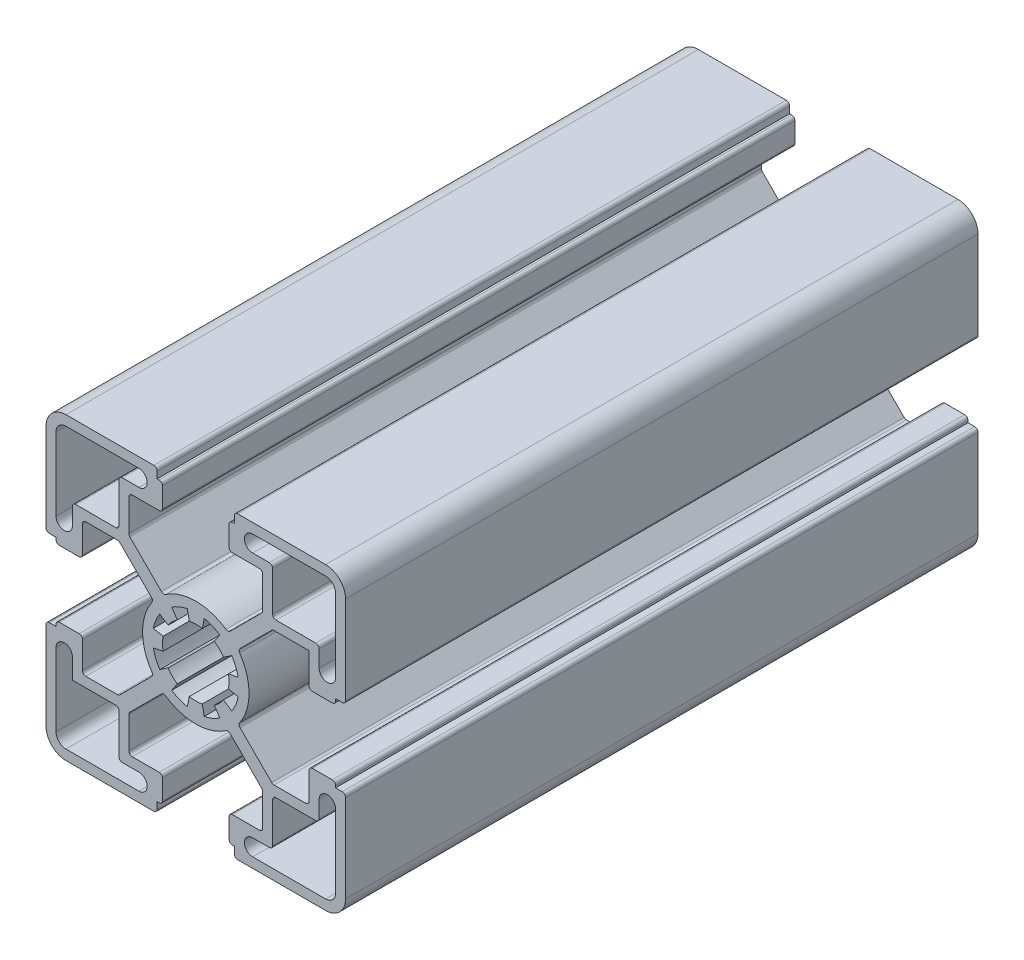
SolidWorks part; units mm, degrees
ref_plane "Front Plane" through (0, 0, 0) normal (0, 0, 1) x (1, 0, 0)
ref_plane "Top Plane" through (0, 0, 0) normal (0, 1, 0) x (1, 0, 0)
ref_plane "Right Plane" through (0, 0, 0) normal (1, 0, 0) x (0, 0, -1)
sketch "Sketch1" plane through (0, 0, 0) normal (0, 0, 1) x (1, 0, 0)
  line L0 (0, 22.5) -> (0, -22.5) construction
  line L1 (22.5, 0) -> (-22.5, 0) construction
  line L2 (-5.8, 22.5) -> (5.8, 22.5) construction
  line L3 (-5, 21) -> (5, 21) construction
  line L4 (-10.05, 10.05) -> (10.05, 10.05) construction
  line L5 (0, 0) -> (-10.05, 10.05) construction
  circle A0 centre (0, 0) radius 5 construction
  point P4 (0, 0)
  point P8 (0, 0)
  point P10 (0, 8)
  point P14 (0, 22.5)
  point P17 (0, 21)
  point P19 (0, 10.05)
sketch "Sketch2" plane through (0, 0, 0) normal (1, 0, 0) x (0, 0, -1)
  line L0 (47.5, 0) -> (-47.5, 0) construction
  point P4 (0, 0)
  dimension "D1" = 95
sketch "Sketch3" plane through (0, 0, 0) normal (0, 0, 1) x (1, 0, 0)
  line L5 (-21, 8.5375) -> (-21, 19.5)
  line L9 (0, 0) -> (-22.5, 22.5) construction
  line L10 (-11.55, -10.05) -> (-6.3569, -4.8569)
  line L11 (-19.5, 21) -> (-8.5375, 21)
  line L38 (-5.8, 22.5) -> (-5.8, 21)
  line L46 (-5.8, 21) -> (-5, 21)
  line L62 (-5, 21) -> (-5, 17.025)
  line L74 (-5, 17.025) -> (-10.05, 17.025)
  line L76 (-10.05, 17.025) -> (-10.05, 11.55)
  line L77 (-10.05, 11.55) -> (-4.8569, 6.3569)
  line L78 (-18.525, 8.5375) -> (-18.525, 11.55)
  line L79 (-10.05, 17.025) -> (-10.05, 22.5) construction
  line L80 (0, 22.5) -> (0, -22.5) construction
  line L81 (-5.8, 22.5) -> (5.8, 22.5) construction
  line L82 (10.05, 11.55) -> (4.8569, 6.3569)
  line L83 (10.05, 17.025) -> (10.05, 11.55)
  line L84 (5, 17.025) -> (10.05, 17.025)
  line L85 (5, 21) -> (5, 17.025)
  line L86 (5.8, 21) -> (5, 21)
  line L87 (5.8, 22.5) -> (5.8, 21)
  line L88 (-22.5, -5.8) -> (-21, -5.8)
  line L89 (-21, -5.8) -> (-21, -5)
  line L90 (-21, -5) -> (-17.025, -5)
  line L91 (-17.025, -5) -> (-17.025, -10.05)
  line L92 (-17.025, -10.05) -> (-11.55, -10.05)
  line L93 (-11.55, -10.05) -> (-6.3569, -4.8569)
  line L94 (-11.55, 10.05) -> (-6.3569, 4.8569)
  line L95 (-17.025, 10.05) -> (-11.55, 10.05)
  line L96 (-17.025, 5) -> (-17.025, 10.05)
  line L97 (-21, 5) -> (-17.025, 5)
  line L98 (-21, 5.8) -> (-21, 5)
  line L99 (-22.5, 5.8) -> (-21, 5.8)
  line L100 (-22.5, 5.8) -> (-22.5, 19.5)
  line L101 (-19.5, 22.5) -> (-5.8, 22.5)
  line L102 (-18.525, 11.55) -> (-11.55, 11.55)
  line L103 (-8.5375, 18.525) -> (-11.55, 18.525)
  line L104 (-11.55, 18.525) -> (-11.55, 11.55)
  line L108 (5.8, -22.5) -> (5.8, -21)
  line L113 (5.8, -21) -> (5, -21)
  line L117 (5.8, 22.5) -> (19.5, 22.5)
  line L118 (22.5, 19.5) -> (22.5, 5.8)
  line L119 (19.5, -22.5) -> (5.8, -22.5)
  line L120 (0, 0) -> (22.5, 0) construction
  line L121 (-22.5, -19.5) -> (-22.5, -5.8)
  line L136 (5, -21) -> (5, -17.025)
  line L137 (5, -17.025) -> (10.05, -17.025)
  line L138 (10.05, -17.025) -> (10.05, -11.55)
  line L139 (10.05, -11.55) -> (4.8569, -6.3569)
  line L140 (-10.05, -11.55) -> (-4.8569, -6.3569)
  line L141 (-10.05, -17.025) -> (-10.05, -11.55)
  line L142 (-5, -17.025) -> (-10.05, -17.025)
  line L143 (-5, -21) -> (-5, -17.025)
  line L144 (-5.8, -21) -> (-5, -21)
  line L145 (-5.8, -22.5) -> (-5.8, -21)
  line L146 (-5.8, -22.5) -> (-19.5, -22.5)
  line L147 (22.5, 5.8) -> (21, 5.8)
  line L148 (21, 5.8) -> (21, 5)
  line L149 (21, 5) -> (17.025, 5)
  line L150 (17.025, 5) -> (17.025, 10.05)
  line L151 (17.025, 10.05) -> (11.55, 10.05)
  line L152 (11.55, 10.05) -> (6.3569, 4.8569)
  line L153 (11.55, -10.05) -> (6.3569, -4.8569)
  line L154 (17.025, -10.05) -> (11.55, -10.05)
  line L155 (17.025, -5) -> (17.025, -10.05)
  line L156 (21, -5) -> (17.025, -5)
  line L157 (21, -5.8) -> (21, -5)
  line L158 (22.5, -5.8) -> (21, -5.8)
  line L159 (11.55, -10.05) -> (6.3569, -4.8569)
  line L160 (22.5, -5.8) -> (22.5, -19.5)
  line L161 (8.5375, 21) -> (19.5, 21)
  line L162 (21, 19.5) -> (21, 8.5375)
  line L163 (8.5375, 18.525) -> (11.55, 18.525)
  line L164 (11.55, 18.525) -> (11.55, 11.55)
  line L165 (18.525, 8.5375) -> (18.525, 11.55)
  line L166 (18.525, 11.55) -> (11.55, 11.55)
  line L167 (21, -8.5375) -> (21, -19.5)
  line L168 (19.5, -21) -> (8.5375, -21)
  line L169 (18.525, -8.5375) -> (18.525, -11.55)
  line L170 (18.525, -11.55) -> (11.55, -11.55)
  line L171 (8.5375, -18.525) -> (11.55, -18.525)
  line L172 (11.55, -18.525) -> (11.55, -11.55)
  line L173 (-8.5375, -21) -> (-19.5, -21)
  line L174 (-21, -19.5) -> (-21, -8.5375)
  line L175 (-8.5375, -18.525) -> (-11.55, -18.525)
  line L176 (-11.55, -18.525) -> (-11.55, -11.55)
  line L177 (-18.525, -8.5375) -> (-18.525, -11.55)
  line L178 (-18.525, -11.55) -> (-11.55, -11.55)
  line L179 (0, 0) -> (-11.55, 11.55) construction
  line L180 (0, 0) -> (11.55, 11.55) construction
  arc A2 (-21, 19.5) -> (-19.5, 21) centre (-19.5, 19.5) cw
  arc A73 (-4.8569, 6.3569) -> (4.8569, 6.3569) centre (0, 0) cw
  arc A74 (-6.3569, 4.8569) -> (-6.3569, -4.8569) centre (0, 0) ccw
  arc A75 (-19.5, 22.5) -> (-22.5, 19.5) centre (-19.5, 19.5) ccw
  arc A76 (-21, 8.5375) -> (-18.525, 8.5375) centre (-19.7625, 8.5375) ccw
  arc A77 (-8.5375, 21) -> (-8.5375, 18.525) centre (-8.5375, 19.7625) cw
  arc A80 (19.5, 22.5) -> (22.5, 19.5) centre (19.5, 19.5) cw
  arc A81 (22.5, -19.5) -> (19.5, -22.5) centre (19.5, -19.5) cw
  arc A82 (-19.5, -22.5) -> (-22.5, -19.5) centre (-19.5, -19.5) cw
  circle A88 centre (0, 0) radius 5 construction
  circle A89 centre (0, 0) radius 5
  arc A90 (-4.8569, -6.3569) -> (4.8569, -6.3569) centre (0, 0) ccw
  arc A91 (19.5, 21) -> (21, 19.5) centre (19.5, 19.5) cw
  arc A92 (6.3569, 4.8569) -> (6.3569, -4.8569) centre (0, 0) cw
  arc A93 (8.5375, 21) -> (8.5375, 18.525) centre (8.5375, 19.7625) ccw
  arc A94 (21, 8.5375) -> (18.525, 8.5375) centre (19.7625, 8.5375) cw
  arc A95 (21, -19.5) -> (19.5, -21) centre (19.5, -19.5) cw
  arc A96 (21, -8.5375) -> (18.525, -8.5375) centre (19.7625, -8.5375) ccw
  arc A97 (8.5375, -21) -> (8.5375, -18.525) centre (8.5375, -19.7625) cw
  arc A98 (-19.5, -21) -> (-21, -19.5) centre (-19.5, -19.5) cw
  arc A99 (-8.5375, -21) -> (-8.5375, -18.525) centre (-8.5375, -19.7625) ccw
  arc A100 (-21, -8.5375) -> (-18.525, -8.5375) centre (-19.7625, -8.5375) cw
  point P54 (-14.2875, 10.05)
  dimension "D2" = 3
  dimension "D3" = 1.5
  dimension "D4" = 1.5
  dimension "D5" = 1.5
  dimension "D6" = 90
  dimension "D1" = 4
extrude "Boss-Extrude1" add sketch "Sketch3" along normal up to vertex (47.5 mm away) and the other way up to vertex (47.5 mm away) contours A92 L152 L151 L150 L149 L148 L147 L118 A80 L117 L87 L86 L85 L84 L83 L82 A73 L77 L76 L74 L62 L46 L38 L101 A75 L100 L99 L98 L97 L96 L95 L94 A74 L10 L92 L91 L90 L89 L88 L121 A82 L146 L145 L144 L143 L142 L141 L140 A90 L139 L138 up to point (0, 0, 47.5) other way up to point (0, 0, -47.5)
fillet "Fillet1" radius 0.5 58 edges at (5, 21, 0) (5.8, 22.5, 0) (-5.8, 22.5, 0) (-5, 21, 0) (-10.05, 17.025, 0) (-5, 17.025, 0) (5, 17.025, 0) (-22.5, -5.8, 0) (-21, -5, 0) (-17.025, -5, 0) (-17.025, -10.05, 0) (-11.55, -10.05, 0) (-6.3569, -4.8569, 0) (-6.3569, 4.8569, 0) (-11.55, 10.05, 0) (-17.025, 10.05, 0) (-17.025, 5, 0) (-22.5, 5.8, 0) (-21, 5, 0) (-18.525, 11.55, 0) (-11.55, 11.55, 0) (-11.55, 18.525, 0) (4.8569, 6.3569, 0) (-4.8569, 6.3569, 0) (-10.05, 11.55, 0) (10.05, 17.025, 0) (10.05, 11.55, 0) (22.5, -5.8, 0) (21, -5, 0) (17.025, -5, 0) (17.025, -10.05, 0) (6.3569, 4.8569, 0) (11.55, 10.05, 0) (22.5, 5.8, 0) (21, 5, 0) (17.025, 5, 0) (4.8569, -6.3569, 0) (11.55, -11.55, 0) (-11.55, -11.55, 0) (18.525, -11.55, 0) (11.55, -18.525, 0) (10.05, -17.025, 0) (5, -17.025, 0) (5, -21, 0) (5.8, -22.5, 0) (-5.8, -22.5, 0) (-5, -21, 0) (-5, -17.025, 0) (-10.05, -17.025, 0) (-11.55, -18.525, 0) (11.55, 18.525, 0) (18.525, 11.55, 0) (11.55, 11.55, 0) (11.55, -10.05, 0) (6.3569, -4.8569, 0) (-4.8569, -6.3569, 0) (10.05, -11.55, 0) (-10.05, -11.55, 0)
sketch "Sketch4" plane through (0, 0, 47.5) normal (0, 0, 1) x (1, 0, 0)
  line L0 (-1.2681, 6.3751) -> (-0.9755, 4.9039)
  line L1 (0, 0) -> (0, 8) construction
  line L2 (-3.6112, 5.4046) -> (-2.7779, 4.1573)
  line L3 (1.2681, 6.3751) -> (0.9755, 4.9039)
  line L4 (3.6112, 5.4046) -> (2.7779, 4.1573)
  line L5 (5.4046, 3.6112) -> (4.1573, 2.7779)
  line L6 (6.3751, 1.2681) -> (4.9039, 0.9755)
  line L7 (6.3751, -1.2681) -> (4.9039, -0.9755)
  line L8 (5.4046, -3.6112) -> (4.1573, -2.7779)
  line L9 (3.6112, -5.4046) -> (2.7779, -4.1573)
  line L10 (1.2681, -6.3751) -> (0.9755, -4.9039)
  line L11 (-1.2681, -6.3751) -> (-0.9755, -4.9039)
  line L12 (-3.6112, -5.4046) -> (-2.7779, -4.1573)
  line L13 (-5.4046, -3.6112) -> (-4.1573, -2.7779)
  line L14 (-6.3751, -1.2681) -> (-4.9039, -0.9755)
  line L15 (-6.3751, 1.2681) -> (-4.9039, 0.9755)
  line L16 (-5.4046, 3.6112) -> (-4.1573, 2.7779)
  line L17 (0, 0) -> (-0.9755, 4.9039) construction
  line L18 (0, 0) -> (2.7779, 4.1573) construction
  arc A0 (-1.2681, 6.3751) -> (-3.6112, 5.4046) centre (0, 0) ccw
  circle A1 centre (0, 0) radius 5 construction
  arc A2 (-0.9755, 4.9039) -> (-2.7779, 4.1573) centre (0, 0) ccw
  arc A4 (2.7779, 4.1573) -> (0.9755, 4.9039) centre (0, 0) ccw
  arc A5 (3.6112, 5.4046) -> (1.2681, 6.3751) centre (0, 0) ccw
  arc A6 (4.9039, 0.9755) -> (4.1573, 2.7779) centre (0, 0) ccw
  arc A7 (6.3751, 1.2681) -> (5.4046, 3.6112) centre (0, 0) ccw
  arc A8 (4.1573, -2.7779) -> (4.9039, -0.9755) centre (0, 0) ccw
  arc A9 (5.4046, -3.6112) -> (6.3751, -1.2681) centre (0, 0) ccw
  arc A10 (0.9755, -4.9039) -> (2.7779, -4.1573) centre (0, 0) ccw
  arc A11 (1.2681, -6.3751) -> (3.6112, -5.4046) centre (0, 0) ccw
  arc A12 (-2.7779, -4.1573) -> (-0.9755, -4.9039) centre (0, 0) ccw
  arc A13 (-3.6112, -5.4046) -> (-1.2681, -6.3751) centre (0, 0) ccw
  arc A14 (-4.9039, -0.9755) -> (-4.1573, -2.7779) centre (0, 0) ccw
  arc A15 (-6.3751, -1.2681) -> (-5.4046, -3.6112) centre (0, 0) ccw
  arc A16 (-4.1573, 2.7779) -> (-4.9039, 0.9755) centre (0, 0) ccw
  arc A17 (-5.4046, 3.6112) -> (-6.3751, 1.2681) centre (0, 0) ccw
  dimension "D1" = 1.5
  dimension "D2" = 22.5
  dimension "D5" = 45
  dimension "D4" = 8
extrude "Cut-Extrude1" cut sketch "Sketch4" against normal through all
equation "\"D3@Sketch3\"=\"Wall@Sketch1\""
equation "\"D4@Sketch3\"=\"Wall@Sketch1\""
equation "\"D5@Sketch3\"=\"Wall@Sketch1\""
equation "\"D1@Sketch4\"=\"Wall@Sketch1\""
